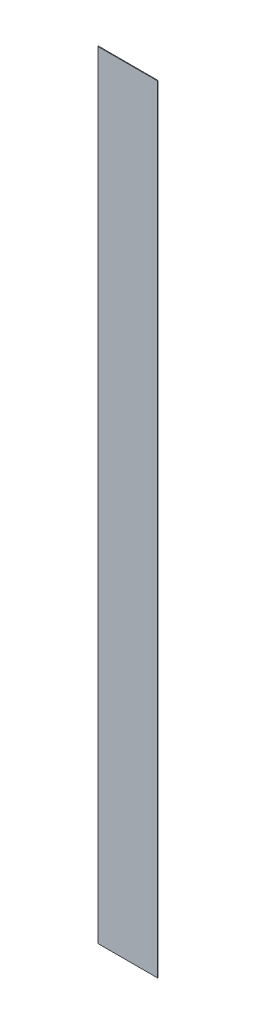
SolidWorks part; units mm, degrees
material "花纹钢板"
ref_plane "前视基准面" through (0, 0, 0) normal (0, 0, 1) x (1, 0, 0)
ref_plane "上视基准面" through (0, 0, 0) normal (0, 1, 0) x (1, 0, 0)
ref_plane "右视基准面" through (0, 0, 0) normal (1, 0, 0) x (0, 0, -1)
sketch "草图1" plane through (0, 0, 0) normal (0, 0, 1) x (1, 0, 0)
  line L1 (-243, 3154) -> (243, 3154)
  line L2 (-243, 3154) -> (-243, -3154)
  line L3 (-243, -3154) -> (243, -3154)
  line L4 (243, 3154) -> (243, -3154)
  line L5 (-243, 3154) -> (243, -3154) construction
  line L6 (-243, -3154) -> (243, 3154) construction
  point P0 (0, 0)
  dimension "D1" = 486
  dimension "D2" = 6308
extrude "凸台-拉伸1" add sketch "草图1" along normal blind 5
